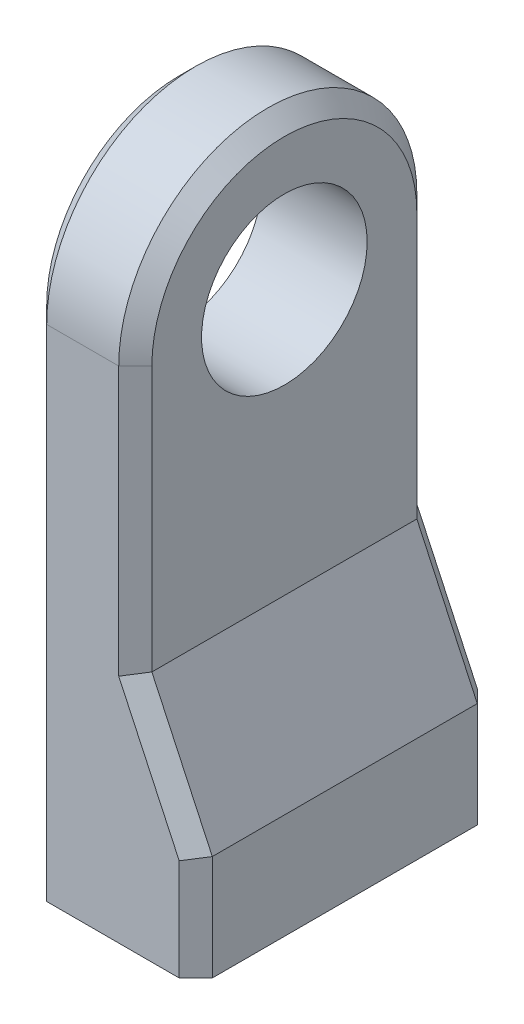
SolidWorks part; units mm, degrees
ref_plane "Front Plane" through (0, 0, 0) normal (0, 0, 1) x (1, 0, 0)
ref_plane "Top Plane" through (0, 0, 0) normal (0, 1, 0) x (1, 0, 0)
ref_plane "Right Plane" through (0, 0, 0) normal (1, 0, 0) x (0, 0, -1)
sketch "Sketch1" plane through (0, 0, 0) normal (1, 0, 0) x (0, 0, -1)
  line L0 (-18, 30.175) -> (-18, 0)
  line L1 (-18, 0) -> (0, 0)
  line L2 (0, 0) -> (0, 30.175)
  arc A0 (0, 30.175) -> (-18, 30.175) centre (-9, 30.175) ccw
  circle A1 centre (-9, 30.175) radius 5
  point P6 (-31.1387, 35)
  point P8 (0, 0)
  dimension "D1" = 10
  dimension "D2" = 9
  dimension "D3" = 30.175
extrude "Boss-Extrude1" add sketch "Sketch1" along normal blind 10
sketch "Sketch2" plane through (0, 0, 0) normal (0, -1, 0) x (1, 0, 0)
  line L0 (5, 18) -> (5, 0) construction
  line L1 (10, 18) -> (0, 18) construction
  line L2 (10, 0) -> (0, 0) construction
  line L3 (0, 9) -> (10, 9) construction
  line L4 (0, 18) -> (0, 0) construction
  line L5 (10, 18) -> (10, 0) construction
  circle A0 centre (5, 4) radius 2
  circle A1 centre (5, 14) radius 2
  dimension "D1" = 4
  dimension "D2" = 4
  dimension "D3" = 5
  dimension "D4" = 5
extrude "Cut-Extrude1" cut sketch "Sketch2" against normal blind 10
sketch "Sketch3" plane through (0, 0, 0) normal (0, 0, 1) x (1, 0, 0)
  line L0 (10, 6.35) -> (6.35, 14.1775)
  line L1 (10, 30.175) -> (10, 0) construction
  line L2 (6.35, 14.1775) -> (6.35, 39.175)
  line L3 (10, 39.175) -> (0, 39.175) construction
  line L4 (6.35, 39.175) -> (10, 39.175)
  line L5 (10, 39.175) -> (10, 6.35)
  line L6 (0, 39.175) -> (0, 30.175) construction
  dimension "D1" = 6.35
  dimension "D2" = 25
  dimension "D3" = 6.35
extrude "Cut-Extrude2" cut sketch "Sketch3" along normal blind 24
chamfer "Chamfer1" distance 1 angle 45 10 edges at (0, 15.0875, 0) (0, 15.0875, 18) (0, 39.175, 9) (10, 3.175, 18) (8.175, 10.2637, 18) (6.35, 22.1762, 18) (6.35, 39.175, 9) (10, 3.175, 0) (8.175, 10.2637, 0) (6.35, 22.1762, 0)
